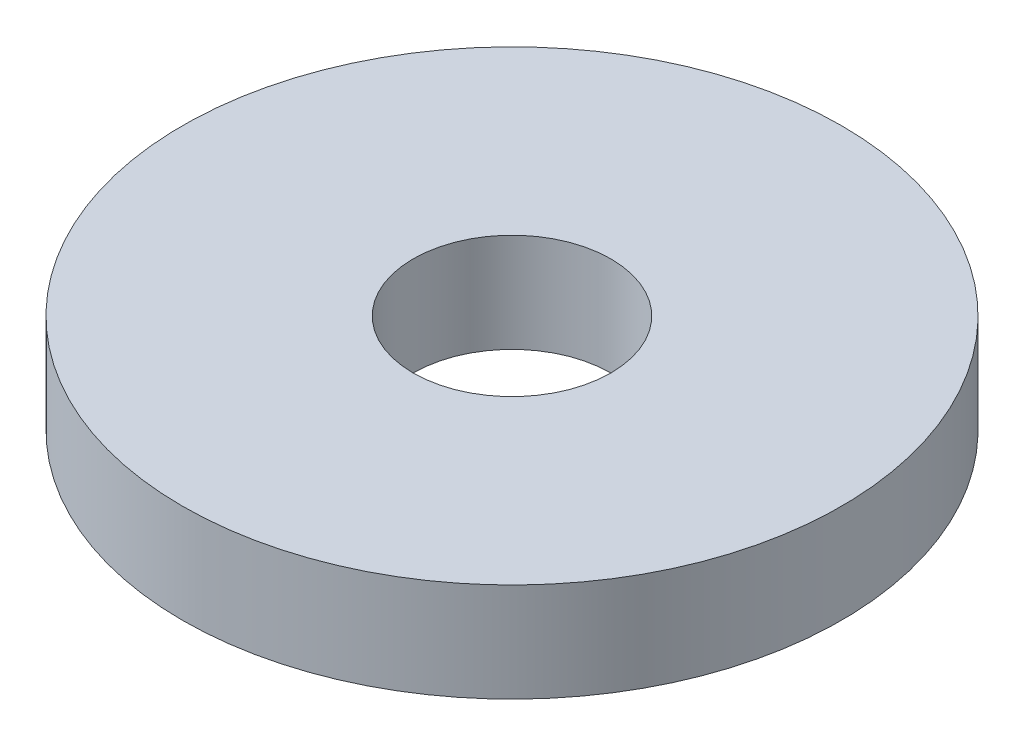
SolidWorks part; units mm, degrees
ref_plane "Plan de face" through (0, 0, 0) normal (0, 0, 1) x (1, 0, 0)
ref_plane "Plan de dessus" through (0, 0, 0) normal (0, 1, 0) x (1, 0, 0)
ref_plane "Plan de droite" through (0, 0, 0) normal (1, 0, 0) x (0, 0, -1)
sketch "Esquisse1" plane through (0, 0, 0) normal (0, 1, 0) x (1, 0, 0)
  circle A0 centre (0, 0) radius 5
  circle A1 centre (0, 0) radius 1.5
  dimension "D1" = 10
  dimension "D2" = 3
extrude "Boss.-Extru.1" add sketch "Esquisse1" along normal blind 1.5
